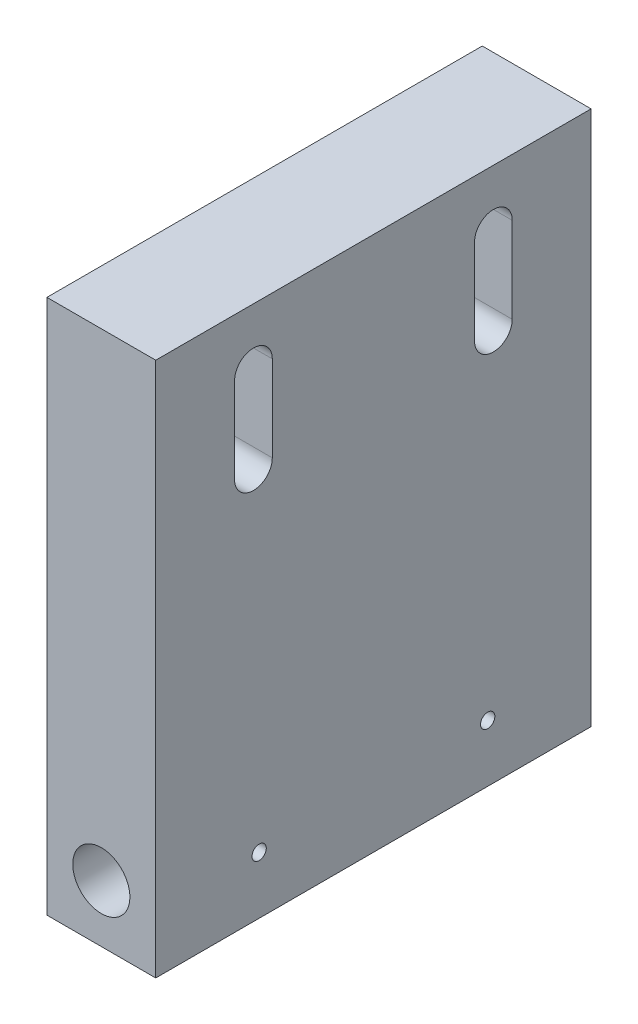
SolidWorks part; units mm, degrees
material "6061-O (SS)"
ref_plane "Alzado" through (0, 0, 0) normal (0, 0, 1) x (1, 0, 0)
ref_plane "Planta" through (0, 0, 0) normal (0, 1, 0) x (1, 0, 0)
ref_plane "Vista lateral" through (0, 0, 0) normal (1, 0, 0) x (0, 0, -1)
sketch "Croquis1" plane through (0, 0, 0) normal (0, 0, 1) x (1, 0, 0)
  line L0 (0, 93.65) -> (0, 0)
  line L1 (0, 0) -> (206.35, 0)
  dimension "D1" = 93.65
  dimension "D2" = 206.35
ref_plane "Plano1" through (0, 0, 0) normal (1, 0, 0) x (0, 1, 0)
other "Al solid profiles 3 X 0.5(1)"
ref_plane "Plano2" through (0, 93.65, 0) normal (0, -1, 0) x (0, 0, 1)
sketch "Croquis11" plane through (0, 93.65, 0) normal (0, -1, 0) x (0, 0, 1)
  line L1 (38.1, 9.525) -> (-38.1, 9.525)
  line L2 (38.1, 9.525) -> (38.1, -9.525)
  line L3 (38.1, -9.525) -> (-38.1, -9.525)
  line L4 (-38.1, 9.525) -> (-38.1, -9.525)
  line L5 (38.1, 9.525) -> (-38.1, -9.525) construction
  line L6 (38.1, -9.525) -> (-38.1, 9.525) construction
  point P0 (0, 0)
  point P5 (0, 0)
  dimension "D1" = 19.05
  dimension "D2" = 76.2
sketch "Croquis12" plane through (9.525, 0, 0) normal (1, 0, 0) x (0, 0, -1)
  line L0 (0, 0) -> (0, 50000) construction
  line L1 (-21, 83.65) -> (-21, 68.65) construction
  line L2 (-17.7, 83.65) -> (-17.7, 68.65)
  line L3 (-24.3, 83.65) -> (-24.3, 68.65)
  line L4 (21, 83.65) -> (21, 68.65) construction
  line L5 (17.7, 83.65) -> (17.7, 68.65)
  line L6 (24.3, 83.65) -> (24.3, 68.65)
  arc A0 (-17.7, 83.65) -> (-24.3, 83.65) centre (-21, 83.65) ccw
  arc A1 (-24.3, 68.65) -> (-17.7, 68.65) centre (-21, 68.65) ccw
  arc A2 (17.7, 83.65) -> (24.3, 83.65) centre (21, 83.65) cw
  arc A3 (24.3, 68.65) -> (17.7, 68.65) centre (21, 68.65) cw
  point P5 (-21, 76.15)
  point P13 (21, 76.15)
  dimension "D1" = 3.3
  dimension "D2" = 10
  dimension "D3" = 15
extrude "Cortar-Extruir1" cut sketch "Croquis12" against normal through all
hole_wizard "Diámetro de taladro Ø10.0 (10)1" positions "Croquis13" profile "Croquis14" hole size "Ø10.0" standard "DIN" end condition through all
sketch "Croquis13" plane through (0, 0, -38.1) normal (0, 0, -1) x (-1, 0, 0)
  line L0 (9.525, 0) -> (-9.525, 0) construction
  point P0 (0, 10)
  point P6 (0, 0)
  dimension "D1" = 10
sketch "Croquis14" plane through (0, 10, -38.1) normal (1, 0, 0) x (0, 1, 0)
  line L0 (0, 0) -> (0, 76.2)
  line L1 (0, 76.2) -> (5, 76.2)
  line L2 (5, 76.2) -> (5, 0)
  line L5 (5, 0) -> (0, 0)
  line L11 (0, -6.35) -> (0, 107.95) construction
  dimension "Diámetro de taladro hasta el siguiente" = 10
  dimension "Profundidad de taladro hasta el siguiente" = 76.2
hole_wizard "Taladro roscado M31" positions "Croquis15" profile "Croquis16" tap size "M3" standard "DIN"
sketch "Croquis15" plane through (9.525, 0, 0) normal (1, 0, 0) x (0, 0, -1)
  line L0 (-38.1, 10) -> (38.1, 10) construction
  line L1 (0, 0) -> (0, 50000) construction
  line L2 (38.1, 0) -> (-38.1, 0) construction
  point P0 (20, 10)
  point P2 (-20, 10)
  point P15 (0, 0)
  dimension "D1" = 20
sketch "Croquis16" plane through (9.525, 10, -20) normal (0, 1, 0) x (0, 0, -1)
  line L0 (0, 0) -> (0, 4.525)
  line L1 (0, 4.525) -> (1.25, 4.525)
  line L2 (1.25, 4.525) -> (1.25, 0)
  line L5 (1.25, 0) -> (0, 0)
  line L11 (0, -6.35) -> (0, 107.95) construction
  dimension "Diámetro de perforador para roscar hasta el siguiente" = 2.5
  dimension "Profundidad de perforador para roscar hasta el siguiente" = 4.525
cosmetic thread "Rosca de taladro1" parameters "D2"=3
cosmetic thread "Rosca de taladro2" parameters "D2"=3
